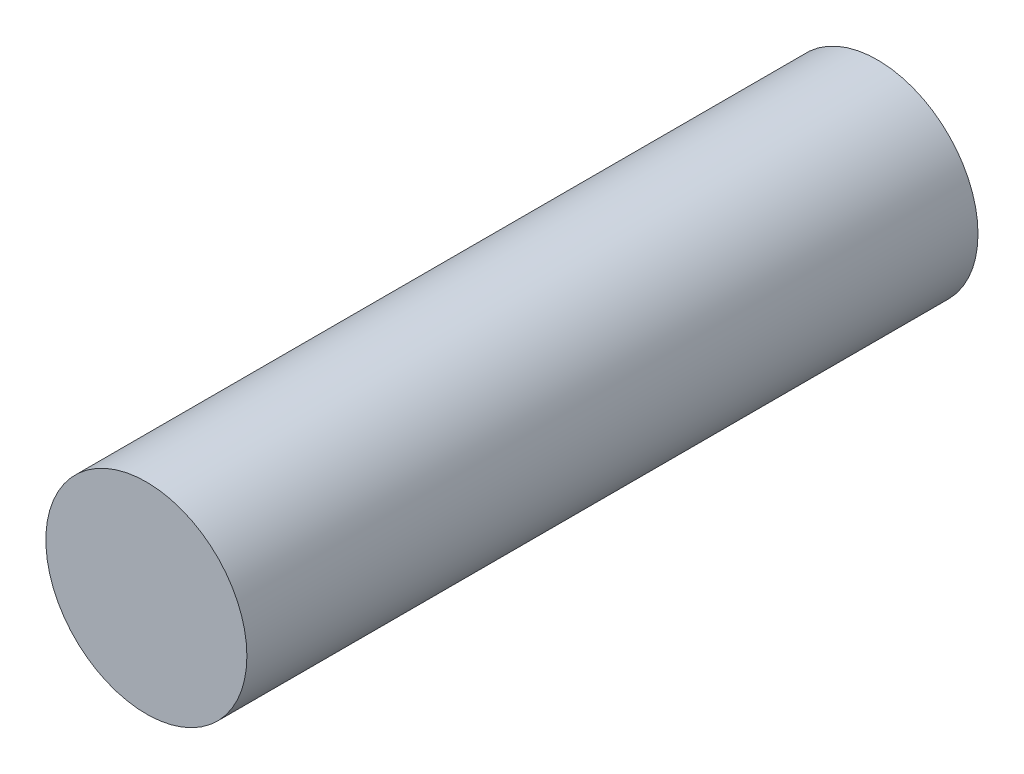
SolidWorks part; units mm, degrees
ref_plane "Front Plane" through (0, 0, 0) normal (0, 0, 1) x (1, 0, 0)
ref_plane "Top Plane" through (0, 0, 0) normal (0, 1, 0) x (1, 0, 0)
ref_plane "Right Plane" through (0, 0, 0) normal (1, 0, 0) x (0, 0, -1)
sketch "Sketch1" plane through (0, 0, 0) normal (0, 0, 1) x (1, 0, 0)
  circle A0 centre (0, 0) radius 69.85
extrude "Boss-Extrude1" add sketch "Sketch1" along normal blind 508
